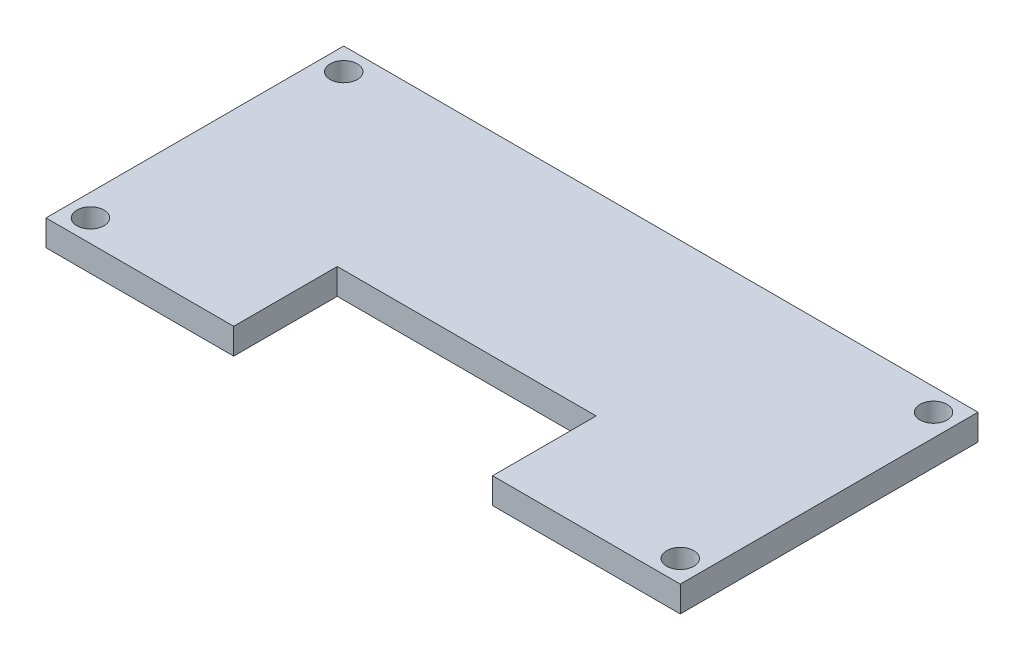
SolidWorks part; units mm, degrees
ref_plane "前视基准面" through (0, 0, 0) normal (0, 0, 1) x (1, 0, 0)
ref_plane "上视基准面" through (0, 0, 0) normal (0, 1, 0) x (1, 0, 0)
ref_plane "右视基准面" through (0, 0, 0) normal (1, 0, 0) x (0, 0, -1)
sketch "草图1" plane through (0, 0, 0) normal (0, 1, 0) x (1, 0, 0)
  line L0 (-22.5, -9.5) -> (-22.5, 9.5) construction
  line L1 (-24.5, -11.5) -> (-10, -11.5)
  line L2 (-24.5, -11.5) -> (-24.5, 11.5)
  line L3 (-24.5, 11.5) -> (24.5, 11.5)
  line L4 (24.5, -11.5) -> (24.5, 11.5)
  line L5 (-24.5, -11.5) -> (24.5, 11.5) construction
  line L6 (-24.5, 11.5) -> (24.5, -11.5) construction
  line L7 (-22.5, 9.5) -> (22.5, 9.5) construction
  line L8 (22.5, -9.5) -> (22.5, 9.5) construction
  line L9 (-22.5, -9.5) -> (22.5, -9.5) construction
  line L10 (-22.5, 9.5) -> (-24.5, 11.5) construction
  line L11 (22.5, 9.5) -> (24.5, 11.5) construction
  line L12 (22.5, -9.5) -> (24.5, -11.5) construction
  line L13 (-22.5, -9.5) -> (-24.5, -11.5) construction
  line L14 (0, -14.2998) -> (0, 19.7209) construction
  line L15 (-30.7898, 0) -> (32.5389, 0) construction
  line L16 (-10, -11.5) -> (-10, -3.5)
  line L17 (-10, -3.5) -> (10, -3.5)
  line L18 (10, -3.5) -> (10, -11.5)
  line L19 (10, -11.5) -> (24.5, -11.5)
  line L21 (-24.5, -11.5) -> (24.5, -11.5) construction
  circle A0 centre (-22.7828, 9.7828) radius 1.05
  circle A1 centre (22.7828, 9.7828) radius 1.05
  circle A2 centre (22.7828, -9.7828) radius 1.05
  circle A3 centre (-22.7828, -9.7828) radius 1.05
  point P0 (0, 0)
  dimension "D4" = 2.1
  dimension "D5" = 0.4
  dimension "D1" = 49
  dimension "D2" = 23
  dimension "D6" = 8
  dimension "D7" = 20
  dimension "D3" = 2
extrude "凸台-拉伸1" add sketch "草图1" along normal blind 2
